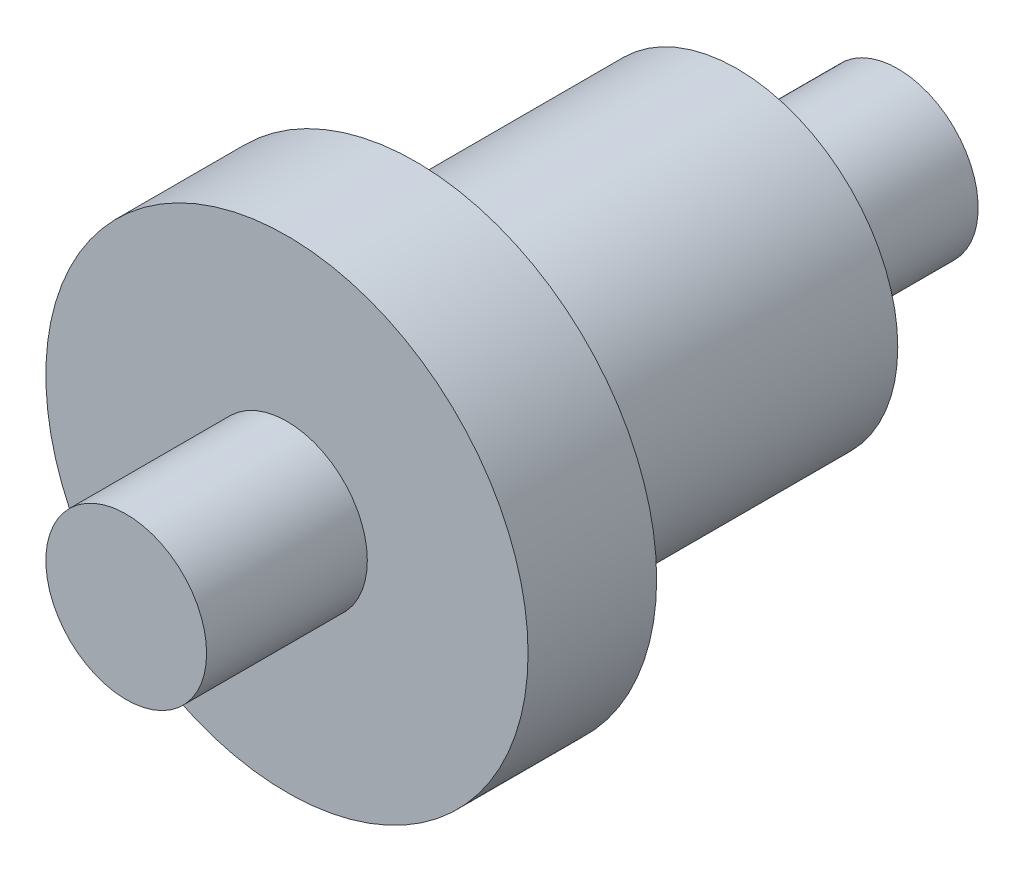
SolidWorks part; units mm, degrees
material "Delrin 2700 NC010, Low Viscosity Acetal Copolymer (SS)"
ref_plane "Front Plane" through (0, 0, 0) normal (0, 0, 1) x (1, 0, 0)
ref_plane "Top Plane" through (0, 0, 0) normal (0, 1, 0) x (1, 0, 0)
ref_plane "Right Plane" through (0, 0, 0) normal (1, 0, 0) x (0, 0, -1)
sketch "Sketch1" plane through (0, 0, 0) normal (0, 0, 1) x (1, 0, 0)
  circle A0 centre (0, 0) radius 9.525
  dimension "D1" = 19.05
extrude "Boss-Extrude1" add sketch "Sketch1" along normal blind 5.08
sketch "Sketch2" plane through (0, 0, 0) normal (0, 0, -1) x (-1, 0, 0)
  circle A0 centre (0, 0) radius 6.35
  dimension "D1" = 12.7
extrude "Boss-Extrude2" add sketch "Sketch2" along normal blind 12.7
sketch "Sketch3" plane through (0, 0, -12.7) normal (0, 0, -1) x (-1, 0, 0)
  circle A0 centre (0, 0) radius 3.175
  dimension "D1" = 6.35
extrude "Boss-Extrude3" add sketch "Sketch3" along normal blind 6.35
sketch "Sketch4" plane through (0, 0, 5.08) normal (0, 0, 1) x (1, 0, 0)
  circle A0 centre (0, 0) radius 3.175
  dimension "D1" = 6.35
extrude "Boss-Extrude4" add sketch "Sketch4" along normal blind 6.35
